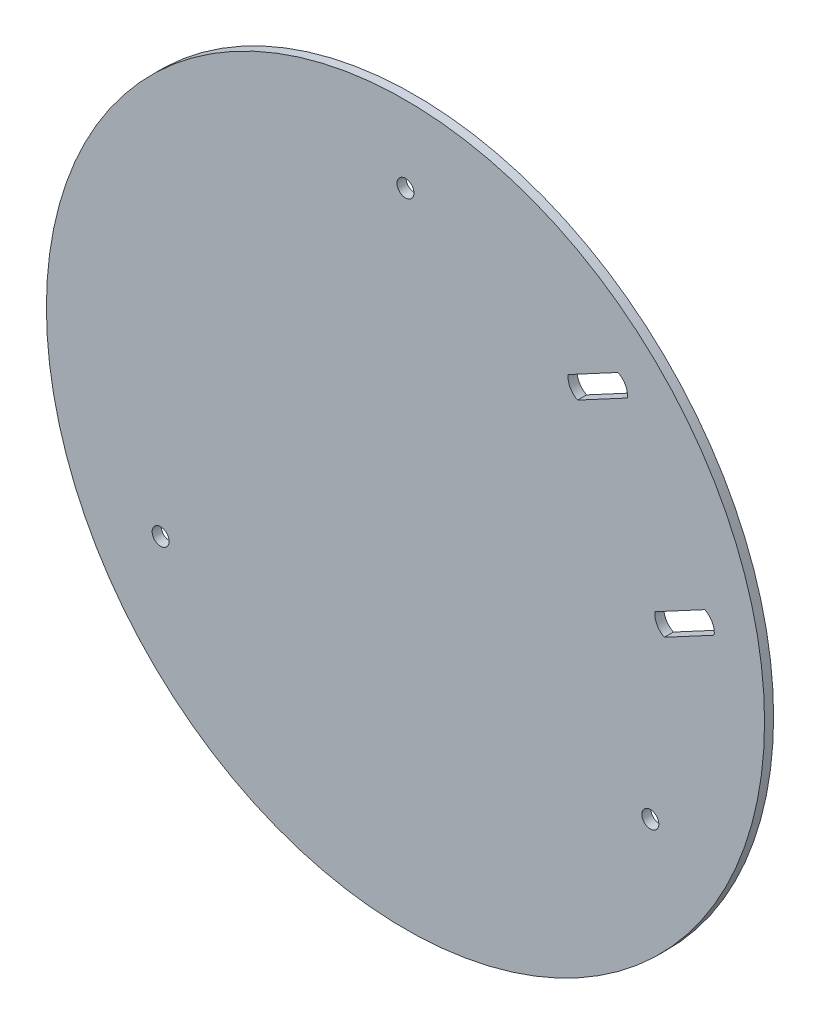
SolidWorks part; units mm, degrees
ref_plane "Front Plane" through (0, 0, 0) normal (0, 0, 1) x (1, 0, 0)
ref_plane "Top Plane" through (0, 0, 0) normal (0, 1, 0) x (1, 0, 0)
ref_plane "Right Plane" through (0, 0, 0) normal (1, 0, 0) x (0, 0, -1)
sketch "Sketch1" plane through (0, 0, 0) normal (0, 0, 1) x (1, 0, 0)
  circle A0 centre (0, 0) radius 63.5
  dimension "D1" = 127
extrude "Boss-Extrude1" add sketch "Sketch1" along normal blind 1.6
sketch "Sketch2" plane through (0, 0, 0) normal (0, 0, -1) x (-1, 0, 0)
  circle A0 centre (0, 0) radius 50
  circle A1 centre (0, 50) radius 1.5
  circle A2 centre (43.3013, -25) radius 1.5
  circle A3 centre (-43.3013, -25) radius 1.5
  point P11 (0, 0)
  dimension "D1" = 100
  dimension "D2" = 3
  dimension "D3" = 3
sketch "Sketch3" plane through (0, 0, 0) normal (0, 0, -1) x (-1, 0, 0)
  circle A0 centre (-34.0063, 36.6548) radius 1.75
  circle A1 centre (-49.3547, 8.0073) radius 1.75
  circle A2 centre (0, 0) radius 63.5 construction
  dimension "D1" = 3.5
  dimension "D2" = 3.5
  dimension "D3" = 32.5
  dimension "D4" = 50
  dimension "D5" = 50
extrude "Cut-Extrude4" cut sketch "Sketch3" against normal blind 1.6
extrude "Cut-Extrude5" cut sketch "Sketch2" against normal blind 1.6 contours A1 | A3 | A2
sketch "Sketch4" plane through (0, 0, 0) normal (0, 0, -1) x (-1, 0, 0)
  line L0 (-34.8328, 35.1122) -> (-48.5282, 9.5498) construction
  line L2 (-52.9355, 11.9111) -> (-44.1209, 7.1886)
  line L3 (-54.5884, 8.826) -> (-45.7738, 4.1034)
  line L6 (-39.2401, 37.4735) -> (-30.4255, 32.7509)
  line L7 (-37.5872, 40.5586) -> (-28.7726, 35.836)
  arc A1 (-45.7738, 4.1034) -> (-44.1209, 7.1886) centre (-47.151, 6.8266) ccw
  circle A2 centre (-34.0063, 36.6548) radius 1.75 construction
  arc A3 (-30.4255, 32.7509) -> (-28.7726, 35.836) centre (-31.8027, 35.4741) ccw
  arc A4 (-39.2401, 37.4735) -> (-37.5872, 40.5586) centre (-36.21, 37.8354) cw
  arc A5 (-54.5884, 8.826) -> (-52.9355, 11.9111) centre (-51.5583, 9.1879) cw
  dimension "D3" = 5
extrude "Cut-Extrude6" cut sketch "Sketch4" against normal blind 10 contours L2 A1 L3 A5 | L6 A3 L7 A4
sketch "Sketch5" plane through (0, 0, 0) normal (0, 0, -1) x (-1, 0, 0)
  line L0 (0, 0) -> (-9.6255, -5.5573) construction
  line L2 (0, -25) -> (0, 0) construction
  line L3 (0, 0) -> (-52.94, 0) construction
  line L4 (-14.8564, 22.282) -> (-11.8686, 24.007)
  line L5 (-23.275, -1.725) -> (-26.725, -1.725)
  line L6 (-23.275, -1.725) -> (-23.275, 1.725)
  line L7 (-23.275, 1.725) -> (-26.725, 1.725)
  line L8 (-26.725, -1.725) -> (-26.725, 1.725)
  line L9 (-23.275, -1.725) -> (-26.725, 1.725) construction
  line L10 (-23.275, 1.725) -> (-26.725, -1.725) construction
  line L11 (-38.515, -1.725) -> (-41.965, -1.725)
  line L12 (-38.515, -1.725) -> (-38.515, 1.725)
  line L13 (-38.515, 1.725) -> (-41.965, 1.725)
  line L14 (-41.965, -1.725) -> (-41.965, 1.725)
  line L15 (-38.515, -1.725) -> (-41.965, 1.725) construction
  line L16 (-38.515, 1.725) -> (-41.965, -1.725) construction
  line L17 (-51.215, -1.725) -> (-54.665, -1.725)
  line L18 (-51.215, -1.725) -> (-51.215, 1.725)
  line L19 (-51.215, 1.725) -> (-54.665, 1.725)
  line L20 (-54.665, -1.725) -> (-54.665, 1.725)
  line L21 (-51.215, -1.725) -> (-54.665, 1.725) construction
  line L22 (-51.215, 1.725) -> (-54.665, -1.725) construction
  line L23 (-10.1436, 21.0192) -> (-11.8686, 24.007)
  line L24 (-13.1314, 19.2942) -> (-14.8564, 22.282)
  line L25 (-13.1314, 19.2942) -> (-10.1436, 21.0192)
  line L26 (-22.4764, 35.4803) -> (-19.4886, 37.2053)
  line L27 (-17.7636, 34.2175) -> (-19.4886, 37.2053)
  line L28 (-20.7514, 32.4925) -> (-17.7636, 34.2175)
  line L29 (-20.7514, 32.4925) -> (-22.4764, 35.4803)
  line L30 (-28.8264, 46.4788) -> (-25.8386, 48.2038)
  line L31 (-27.1014, 43.491) -> (-28.8264, 46.4788)
  line L32 (-24.1136, 45.216) -> (-25.8386, 48.2038)
  line L33 (-27.1014, 43.491) -> (-24.1136, 45.216)
  line L34 (11.8686, 24.007) -> (14.8564, 22.282)
  line L35 (13.1314, 19.2942) -> (14.8564, 22.282)
  line L36 (10.1436, 21.0192) -> (11.8686, 24.007)
  line L37 (10.1436, 21.0192) -> (13.1314, 19.2942)
  line L38 (19.4886, 37.2053) -> (22.4764, 35.4803)
  line L39 (20.7514, 32.4925) -> (22.4764, 35.4803)
  line L40 (17.7636, 34.2175) -> (20.7514, 32.4925)
  line L41 (17.7636, 34.2175) -> (19.4886, 37.2053)
  line L42 (25.8386, 48.2038) -> (28.8264, 46.4788)
  line L43 (24.1136, 45.216) -> (25.8386, 48.2038)
  line L44 (27.1014, 43.491) -> (28.8264, 46.4788)
  line L45 (24.1136, 45.216) -> (27.1014, 43.491)
  line L46 (26.725, 1.725) -> (26.725, -1.725)
  line L47 (23.275, -1.725) -> (26.725, -1.725)
  line L48 (23.275, 1.725) -> (26.725, 1.725)
  line L49 (23.275, 1.725) -> (23.275, -1.725)
  line L50 (41.965, 1.725) -> (41.965, -1.725)
  line L51 (38.515, -1.725) -> (41.965, -1.725)
  line L52 (38.515, 1.725) -> (38.515, -1.725)
  line L53 (38.515, 1.725) -> (41.965, 1.725)
  line L54 (54.665, 1.725) -> (54.665, -1.725)
  line L55 (51.215, 1.725) -> (54.665, 1.725)
  line L56 (51.215, -1.725) -> (54.665, -1.725)
  line L57 (51.215, 1.725) -> (51.215, -1.725)
  line L62 (22.4764, -35.4803) -> (19.4886, -37.2053)
  line L63 (17.7636, -34.2175) -> (19.4886, -37.2053)
  line L64 (20.7514, -32.4925) -> (17.7636, -34.2175)
  line L65 (20.7514, -32.4925) -> (22.4764, -35.4803)
  line L66 (28.8264, -46.4788) -> (25.8386, -48.2038)
  line L67 (27.1014, -43.491) -> (28.8264, -46.4788)
  line L68 (24.1136, -45.216) -> (25.8386, -48.2038)
  line L69 (27.1014, -43.491) -> (24.1136, -45.216)
  line L74 (-19.4886, -37.2053) -> (-22.4764, -35.4803)
  line L75 (-20.7514, -32.4925) -> (-22.4764, -35.4803)
  line L76 (-17.7636, -34.2175) -> (-20.7514, -32.4925)
  line L77 (-17.7636, -34.2175) -> (-19.4886, -37.2053)
  line L78 (-25.8386, -48.2038) -> (-28.8264, -46.4788)
  line L79 (-24.1136, -45.216) -> (-25.8386, -48.2038)
  line L80 (-27.1014, -43.491) -> (-28.8264, -46.4788)
  line L81 (-24.1136, -45.216) -> (-27.1014, -43.491)
  line L82 (0, 0) -> (26.6205, -46.108) construction
  line L83 (26.6205, -46.108) -> (27.7715, -44.6516) construction
  line L84 (43.3013, -25) -> (0, 0) construction
  line L85 (0, 0) -> (27.3325, 47.3413) construction
  line L87 (0, 50) -> (0, 0) construction
  line L88 (0, 0) -> (54.665, 0) construction
  line L89 (-28.8264, 46.4788) -> (-24.1136, 45.216) construction
  line L90 (-27.1014, 43.491) -> (-25.8386, 48.2038) construction
  line L91 (-22.4764, 35.4803) -> (-17.7636, 34.2175) construction
  line L92 (-19.4886, 37.2053) -> (-20.7514, 32.4925) construction
  line L93 (-14.8564, 22.282) -> (-10.1436, 21.0192) construction
  line L94 (-11.8686, 24.007) -> (-13.1314, 19.2942) construction
  line L95 (41.965, 1.725) -> (38.515, -1.725) construction
  line L96 (38.515, 1.725) -> (41.965, -1.725) construction
  line L97 (23.275, 1.725) -> (26.725, -1.725) construction
  line L98 (26.725, 1.725) -> (23.275, -1.725) construction
  line L99 (19.4886, 37.2053) -> (20.7514, 32.4925) construction
  line L100 (22.4764, 35.4803) -> (17.7636, 34.2175) construction
  line L101 (25.8386, 48.2038) -> (27.1014, 43.491) construction
  line L102 (24.1136, 45.216) -> (28.8264, 46.4788) construction
  line L103 (11.8686, 24.007) -> (13.1314, 19.2942) construction
  line L104 (10.1436, 21.0192) -> (14.8564, 22.282) construction
  line L105 (51.215, 1.725) -> (54.665, -1.725)
  line L106 (54.665, 1.725) -> (51.215, -1.725)
  line L108 (-10.7265, -21.1754) -> (-10.1436, -21.0192) construction
  line L109 (-20.7514, -32.4925) -> (-19.4886, -37.2053) construction
  line L110 (-22.4764, -35.4803) -> (-17.7636, -34.2175) construction
  line L111 (-27.1014, -43.491) -> (-25.8386, -48.2038) construction
  line L112 (-28.8264, -46.4788) -> (-24.1136, -45.216) construction
  line L115 (20.7514, -32.4925) -> (19.4886, -37.2053) construction
  line L116 (17.7636, -34.2175) -> (22.4764, -35.4803) construction
  line L117 (27.1014, -43.491) -> (25.8386, -48.2038) construction
  line L118 (24.1136, -45.216) -> (28.8264, -46.4788) construction
  line L119 (-11.8686, -24.007) -> (-14.8564, -22.282)
  line L120 (-13.1314, -19.2942) -> (-14.8564, -22.282)
  line L121 (-10.1436, -21.0192) -> (-10.4712, -21.5867)
  line L122 (-10.1436, -21.0192) -> (-10.5669, -20.7749)
  line L123 (10.1436, -21.0192) -> (11.8686, -24.007)
  line L124 (14.8564, -22.282) -> (13.3625, -23.1445)
  line L125 (13.1314, -19.2942) -> (11.6375, -20.1567)
  line L126 (13.1314, -19.2942) -> (14.8564, -22.282)
  circle A0 centre (0, 0) radius 11.1146
  circle A1 centre (0, 0) radius 11.1146
  circle A2 centre (0, 0) radius 11.1146
  circle A3 centre (0, 0) radius 11.1146
  circle A4 centre (0, 0) radius 11.1146
  circle A5 centre (0, 0) radius 11.1146
  circle A7 centre (-10.2194, -21.1455) radius 0.508
  circle A8 centre (-10.2194, -23.6855) radius 0.508
  circle A9 centre (-10.2194, -26.2255) radius 0.508
  circle A10 centre (-10.2194, -28.7655) radius 0.508
  circle A11 centre (-10.2194, -31.3055) radius 0.508
  circle A12 centre (-10.2194, -33.8455) radius 0.508
  circle A13 centre (-10.2194, -36.3855) radius 0.508
  circle A14 centre (-10.2194, -38.9255) radius 0.508
  circle A15 centre (-10.2194, -41.4655) radius 0.508
  circle A16 centre (-10.2194, -44.0055) radius 0.508
  circle A17 centre (-10.2194, -46.5455) radius 0.508
  circle A18 centre (-10.2194, -49.0855) radius 0.508
  circle A19 centre (-10.2194, -51.6255) radius 0.508
  circle A20 centre (-10.2194, -54.1655) radius 0.508
  circle A21 centre (-10.2194, -56.7055) radius 0.508
  circle A22 centre (-10.2194, -59.2455) radius 0.508
  circle A23 centre (10.1006, -59.2455) radius 0.508
  circle A24 centre (10.1006, -56.7055) radius 0.508
  circle A25 centre (10.1006, -54.1655) radius 0.508
  circle A26 centre (10.1006, -51.6255) radius 0.508
  circle A27 centre (10.1006, -49.0855) radius 0.508
  circle A28 centre (10.1006, -46.5455) radius 0.508
  circle A29 centre (10.1006, -44.0055) radius 0.508
  circle A30 centre (10.1006, -41.4655) radius 0.508
  circle A31 centre (10.1006, -38.9255) radius 0.508
  circle A32 centre (10.1006, -31.3055) radius 0.508
  circle A33 centre (10.1006, -33.8455) radius 0.508
  circle A34 centre (10.1006, -36.3855) radius 0.508
  point P4 (-25, 0)
  point P11 (-40.24, 0)
  point P89 (0, 0)
  dimension "D12" = 1.016
  dimension "D13" = 1.016
  dimension "D14" = 2.54
  dimension "D1" = 12.7
  dimension "D2" = 15.24
  dimension "D3" = 25
  dimension "D4" = 3.45
  dimension "D5" = 3.45
  dimension "D7" = 30
  dimension "D8" = 30
  dimension "D9" = 60
  dimension "D15" = 15
  dimension "D16" = 2
  dimension "D6" = 6
